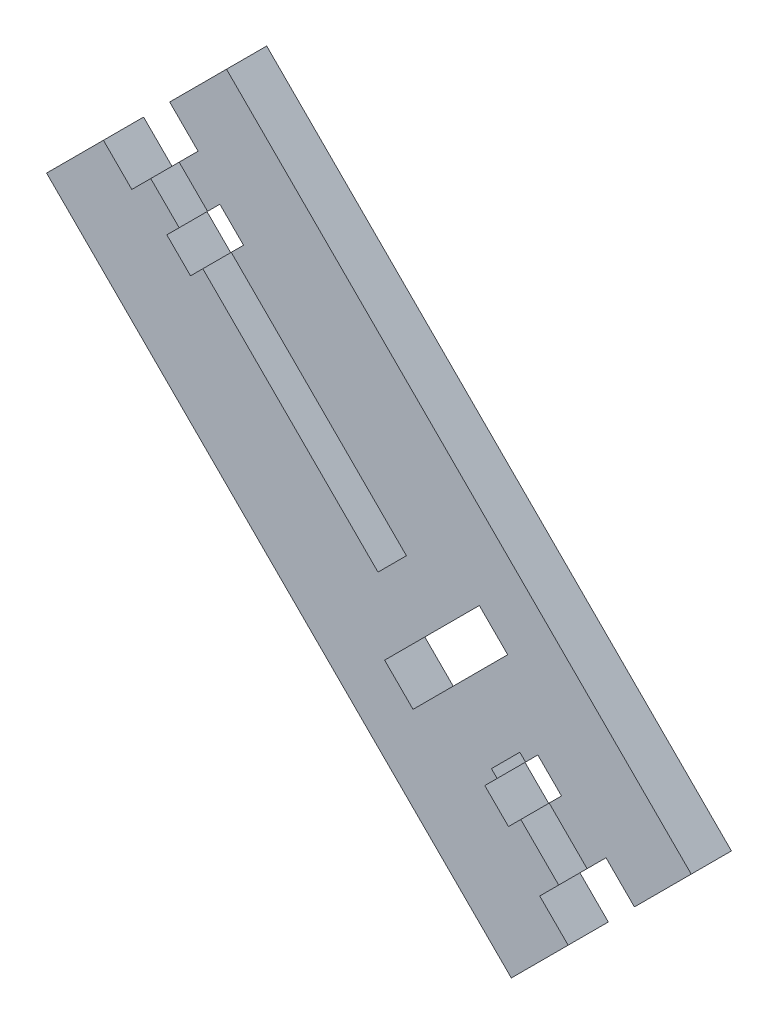
SolidWorks part; units mm, degrees
ref_plane "前基準面" through (0, 0, 0) normal (0, 0, 1) x (1, 0, 0)
ref_plane "上基準面" through (0, 0, 0) normal (0, 1, 0) x (1, 0, 0)
ref_plane "右基準面" through (0, 0, 0) normal (1, 0, 0) x (0, 0, -1)
sketch "草圖1" plane through (0, 0, 0) normal (0, 0, 1) x (1, 0, 0)
  line L0 (94.6091, 74.0325) -> (105.9228, 85.3462) construction
  line L1 (140.6276, 50.6414) -> (129.3139, 39.3277) construction
  line L2 (124.3641, 34.378) -> (120.1214, 30.1354) construction
  line L3 (122.2429, 36.4993) -> (124.3642, 34.378) construction
  line L4 (123.6571, 37.9135) -> (122.2429, 36.4993) construction
  line L5 (129.3139, 39.3277) -> (127.1926, 41.449) construction
  line L6 (127.1926, 41.449) -> (125.7784, 40.0348) construction
  line L7 (119.0609, 42.5097) -> (118.1417, 41.5904) construction
  line L8 (118.6366, 42.9339) -> (119.0609, 42.5097) construction
  line L9 (121.1822, 44.631) -> (120.7579, 45.0553) construction
  line L10 (122.1014, 45.5502) -> (121.1822, 44.631) construction
  line L11 (123.8692, 43.7825) -> (122.1014, 45.5502) construction
  line L12 (122.95, 42.8632) -> (123.8692, 43.7825) construction
  line L13 (125.7784, 40.0348) -> (122.95, 42.8632) construction
  line L14 (120.8287, 40.7419) -> (123.6571, 37.9135) construction
  line L15 (119.9094, 39.8227) -> (120.8287, 40.7419) construction
  line L16 (118.1417, 41.5904) -> (119.9094, 39.8227) construction
  line L17 (120.7579, 45.0553) -> (118.6366, 42.9339) construction
  line L18 (119.8528, 50.91) -> (117.7315, 53.0314) construction
  line L19 (110.6605, 45.9604) -> (112.7818, 43.839) construction
  line L20 (112.7818, 43.839) -> (119.8528, 50.91) construction
  line L21 (117.7315, 53.0314) -> (110.6605, 45.9604) construction
  line L22 (110.1655, 51.4051) -> (112.2868, 53.5264) construction
  line L23 (112.2868, 53.5264) -> (99.2053, 66.6079) construction
  line L24 (97.4376, 68.3756) -> (95.3162, 70.497) construction
  line L25 (96.7305, 71.9112) -> (94.6091, 74.0325) construction
  line L26 (98.3568, 69.2949) -> (97.4376, 68.3756) construction
  line L27 (100.1246, 67.5271) -> (98.3568, 69.2949) construction
  line L28 (99.2053, 66.6079) -> (100.1246, 67.5271) construction
  line L29 (97.084, 64.4866) -> (110.1655, 51.4051) construction
  line L30 (96.1648, 63.5673) -> (97.084, 64.4866) construction
  line L31 (94.397, 65.3351) -> (96.1648, 63.5673) construction
  line L32 (93.1949, 68.3756) -> (95.3162, 66.2543) construction
  line L33 (91.7807, 66.9614) -> (93.1949, 68.3756) construction
  line L34 (89.6594, 69.0828) -> (91.7807, 66.9614) construction
  line L35 (85.4167, 64.8401) -> (89.6594, 69.0828) construction
  line L36 (120.1214, 30.1354) -> (85.4167, 64.8401) construction
  line L37 (94.6091, 74.0325) -> (98.8518, 78.2751)
  line L38 (133.5566, 43.5703) -> (129.3139, 39.3277)
  line L39 (124.3641, 34.378) -> (120.1214, 30.1354)
  line L40 (122.2429, 36.4993) -> (124.3642, 34.378)
  line L41 (123.6571, 37.9135) -> (122.2429, 36.4993)
  line L42 (129.3139, 39.3277) -> (127.1926, 41.449)
  line L43 (127.1926, 41.449) -> (125.7784, 40.0348)
  line L44 (119.0609, 42.5097) -> (118.1417, 41.5904)
  line L45 (118.6366, 42.9339) -> (119.0609, 42.5097)
  line L46 (121.1822, 44.631) -> (120.7579, 45.0553)
  line L47 (122.1014, 45.5502) -> (121.1822, 44.631)
  line L48 (123.8692, 43.7825) -> (122.1014, 45.5502)
  line L49 (122.95, 42.8632) -> (123.8692, 43.7825)
  line L50 (125.7784, 40.0348) -> (122.95, 42.8632)
  line L51 (120.8287, 40.7419) -> (123.6571, 37.9135)
  line L52 (119.9094, 39.8227) -> (120.8287, 40.7419)
  line L53 (118.1417, 41.5904) -> (119.9094, 39.8227)
  line L54 (120.7579, 45.0553) -> (118.6366, 42.9339)
  line L55 (119.8528, 50.91) -> (117.7315, 53.0314)
  line L56 (110.6605, 45.9604) -> (112.7818, 43.839)
  line L57 (112.7818, 43.839) -> (119.8528, 50.91)
  line L58 (117.7315, 53.0314) -> (110.6605, 45.9604)
  line L59 (110.1655, 51.4051) -> (112.2868, 53.5264)
  line L60 (112.2868, 53.5264) -> (99.2053, 66.6079)
  line L61 (97.4376, 68.3756) -> (95.3162, 70.497)
  line L62 (96.7305, 71.9112) -> (94.6091, 74.0325)
  line L63 (98.3568, 69.2949) -> (97.4376, 68.3756)
  line L64 (100.1246, 67.5271) -> (98.3568, 69.2949)
  line L65 (99.2053, 66.6079) -> (100.1246, 67.5271)
  line L66 (97.084, 64.4866) -> (110.1655, 51.4051)
  line L67 (96.1648, 63.5673) -> (97.084, 64.4866)
  line L68 (94.397, 65.3351) -> (96.1648, 63.5673)
  line L69 (93.1949, 68.3756) -> (95.3162, 66.2543)
  line L70 (91.7807, 66.9614) -> (93.1949, 68.3756)
  line L71 (89.6594, 69.0828) -> (91.7807, 66.9614)
  line L72 (85.4167, 64.8401) -> (89.6594, 69.0828)
  line L73 (120.1214, 30.1354) -> (85.4167, 64.8401)
  line L74 (98.8518, 78.2751) -> (133.5566, 43.5703)
  line L75 (96.7305, 71.9112) -> (95.3162, 70.497)
  line L76 (95.3162, 66.2543) -> (94.397, 65.3351)
  point P0 (119.0609, 42.5097)
  point P2 (94.397, 65.3351)
extrude "填料-伸長1" add sketch "草圖1" along normal blind 3 contours L76 L69 L70 L71 L72 L73 L39 L40 L41 L51 L52 L53 L44 L45 L54 L46 L47 L48 L49 L50 L43 L42 L38 L74 L37 L62 L75 L61 L63 L64 L65 L60 L59 L66 L67 L68 L58 L55 L57 L56
